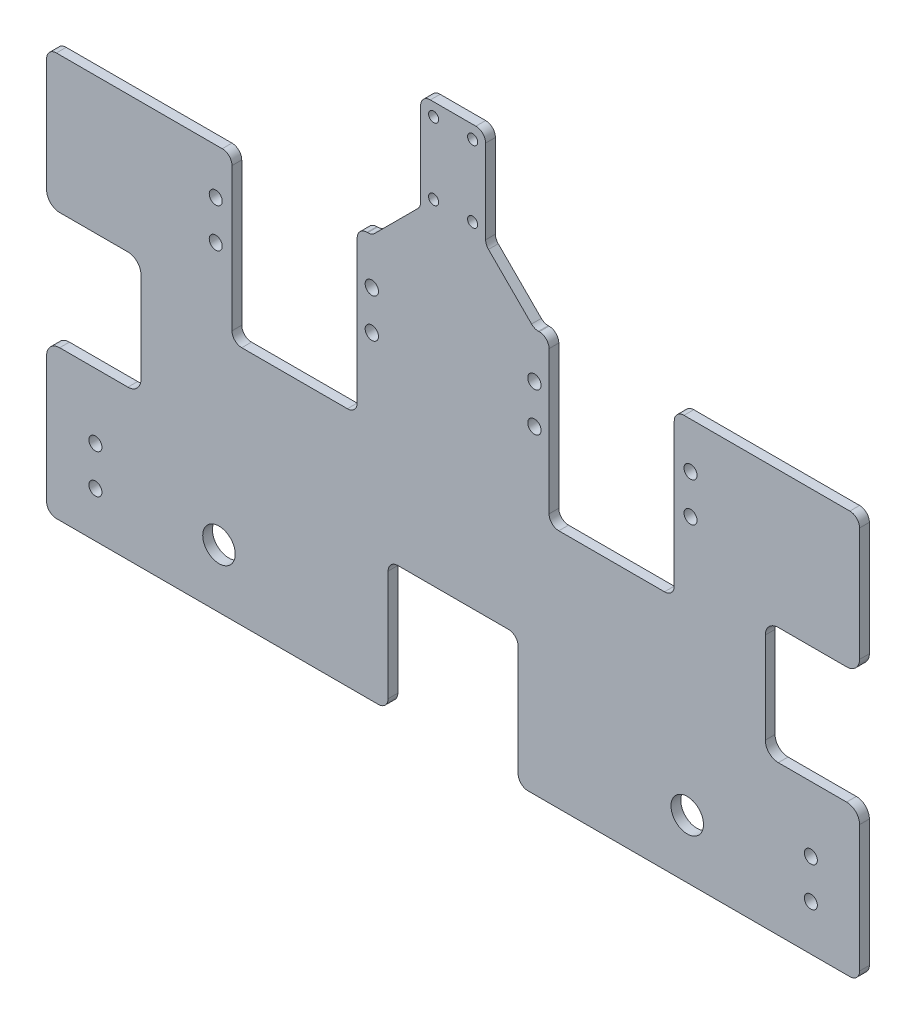
SolidWorks part; units mm, degrees
material "Thornel Mat VMA"
ref_plane "前视基准面" through (0, 0, 0) normal (0, 0, 1) x (1, 0, 0)
ref_plane "上视基准面" through (0, 0, 0) normal (0, 1, 0) x (1, 0, 0)
ref_plane "右视基准面" through (0, 0, 0) normal (1, 0, 0) x (0, 0, -1)
other "Configuration Table"
sketch "草图1" plane through (0, 0, 0) normal (0, 0, 1) x (1, 0, 0)
  line L0 (-32.5, 40) -> (-25, 40)
  line L1 (-25, 40) -> (-10, 55)
  line L2 (-10, 55) -> (-10, 85)
  line L3 (-10, 85) -> (10, 85)
  line L4 (-32.5, 40) -> (-32.5, 0)
  line L5 (-32.5, 0) -> (32.5, 0)
  line L6 (0, 0) -> (0, 50.9699) construction
  line L7 (32.5, 40) -> (32.5, 0)
  line L8 (10, 55) -> (10, 85)
  line L9 (25, 40) -> (10, 55)
  line L10 (32.5, 40) -> (25, 40)
  dimension "D1" = 65
  dimension "D2" = 85
  dimension "D3" = 30
  dimension "D4" = 40
  dimension "D5" = 50
  dimension "D6" = 20
extrude "凸台-拉伸1" add sketch "草图1" along normal blind 3
sketch "草图2" plane through (0, 0, 3) normal (0, 0, 1) x (1, 0, 0)
  line L0 (0, 85) -> (0, 65.679) construction
  line L1 (10, 85) -> (-10, 85) construction
  line L2 (-10, 70) -> (13.1812, 70) construction
  line L3 (-10, 85) -> (-10, 55) construction
  circle A0 centre (-6, 81) radius 1.55
  circle A2 centre (-6, 59) radius 1.55
  circle A3 centre (6, 59) radius 1.55
  circle A4 centre (6, 81) radius 1.55
  dimension "D1" = 4
  dimension "D2" = 4
  dimension "D3" = 3.1
extrude "切除-拉伸1" cut sketch "草图2" against normal through all
sketch "草图3" plane through (0, 0, 3) normal (0, 0, 1) x (1, 0, 0)
  line L0 (32.5, 20) -> (-48.6379, 20) construction
  line L1 (32.5, 0) -> (32.5, 40) construction
  line L2 (0, 0) -> (0, 100.1432) construction
  circle A0 centre (-25, 26) radius 2.05
  circle A2 centre (-25, 14) radius 2.05
  circle A3 centre (25, 14) radius 2.05
  circle A4 centre (25, 26) radius 2.05
  dimension "D1" = 12
  dimension "D2" = 50
  dimension "D3" = 4.1
extrude "切除-拉伸2" cut sketch "草图3" against normal through all
sketch "草图4" plane through (0, 0, 3) normal (0, 0, 1) x (1, 0, 0)
  line L0 (32.5, 0) -> (32.5, 40) construction
  line L1 (32.5, 40) -> (29.5, 40)
  line L2 (32.5, 40) -> (32.5, -0.4765)
  line L3 (32.5, -0.4765) -> (29.5, -0.4765)
  line L4 (29.5, 40) -> (29.5, -0.4765)
  line L5 (0, 85) -> (0, -21.7177) construction
  line L6 (10, 85) -> (-10, 85) construction
  line L7 (-29.5, 40) -> (-29.5, -0.4765)
  line L8 (-32.5, -0.4765) -> (-29.5, -0.4765)
  line L9 (-32.5, 40) -> (-32.5, -0.4765)
  line L10 (-32.5, 40) -> (-29.5, 40)
  dimension "D1" = 3
extrude "切除-拉伸3" cut sketch "草图4" against normal blind 10
sketch "草图5" plane through (0, 0, 3) normal (0, 0, 1) x (1, 0, 0)
  line L0 (0, 0) -> (0, -185.4243) construction
  line L1 (-125, -10) -> (125, -10)
  line L2 (0, 0) -> (0, -84)
  line L3 (-125, -84) -> (125, -84)
  line L4 (125, -10) -> (125, -84)
  line L5 (-125, -10) -> (-125, -84)
  line L6 (-68, -10) -> (-68, 40)
  line L7 (125, -10) -> (68, -10)
  line L8 (125, -10) -> (125, 40)
  line L9 (125, 40) -> (68, 40)
  line L10 (68, -10) -> (68, 40)
  line L11 (-125, 40) -> (-68, 40)
  line L12 (-125, -10) -> (-125, 40)
  line L13 (-125, -10) -> (-68, -10)
  line L14 (-125, -10) -> (-125, -84)
  line L16 (29.5, 40) -> (29.5, 0) construction
  line L17 (-29.5, 0) -> (29.5, 0)
  line L18 (-29.5, 0) -> (-29.5, -10)
  line L19 (-29.5, -10) -> (29.5, -10)
  line L20 (29.5, 0) -> (29.5, -10)
  line M16 (-29.5, 0) -> (29.5, 0)
  dimension "D1" = 250
  dimension "D2" = 50
  dimension "D3" = 68
  dimension "D4" = 74
  dimension "D5" = 10
extrude "凸台-拉伸2" add sketch "草图5" against normal blind 3 contours L10 L1 L8 L9 | L4 L1 L2 L3 | L1 L5 L3 L2 M16 | L12 L1 L6 L11 | L18 L1 L2 M16 | L20 L2 L1 M16
sketch "草图6" plane through (0, 0, 3) normal (0, 0, 1) x (1, 0, 0)
  line L0 (0, 0) -> (0, -103.0936) construction
  line L1 (-125, -84) -> (125, -84) construction
  line L2 (-20, -84) -> (20, -84)
  line L3 (0, -84) -> (0, -44)
  line L4 (-20, -44) -> (20, -44)
  line L5 (20, -84) -> (20, -44)
  line L6 (-20, -84) -> (-20, -44)
  line M14 (-125, -84) -> (125, -84)
  dimension "D1" = 20
  dimension "D2" = 40
extrude "切除-拉伸4" cut sketch "草图6" against normal blind 4 contours L2 L5 L4 L3 | L6 L3 L4 M14
fillet "圆角1" radius 3 22 edges at (-20, -44, 1.5) (20, -44, 1.5) (20, -84, 1.5) (125, -84, 1.5) (68, 40, 1.5) (68, -10, 1.5) (29.5, -10, 1.5) (29.5, 40, 1.5) (25, 40, 1.5) (10, 55, 1.5) (10, 85, 1.5) (-10, 85, 1.5) (-10, 55, 1.5) (-25, 40, 1.5) (-29.5, 40, 1.5) (-29.5, -10, 1.5) (-68, -10, 1.5) (-68, 40, 1.5) (-125, 40, 1.5) (-125, -84, 1.5) (-20, -84, 1.5) (125, 40, 1.5)
sketch "草图7" plane through (0, 0, 3) normal (0, 0, 1) x (1, 0, 0)
  line L0 (125, -81) -> (125, 37) construction
  line L1 (23, -84) -> (122, -84) construction
  line L2 (0, 0) -> (0, -96.374) construction
  line L3 (122, 40) -> (71, 40) construction
  line L4 (96, -2) -> (127, -2)
  line L5 (96, -2) -> (96, -38)
  line L6 (96, -38) -> (127, -38)
  line L7 (127, -2) -> (127, -38)
  line L8 (-127, -2) -> (-127, -38)
  line L9 (-96, -38) -> (-127, -38)
  line L10 (-96, -2) -> (-96, -38)
  line L11 (-96, -2) -> (-127, -2)
  circle A0 centre (72, -66) radius 5
  circle A1 centre (-72, -66) radius 5
  dimension "D1" = 53
  dimension "D2" = 10
  dimension "D3" = 18
  dimension "D4" = 42
  dimension "D5" = 29
  dimension "D6" = 36
  dimension "D7" = 31
extrude "切除-拉伸5" cut sketch "草图7" against normal blind 4
sketch "草图8" plane through (0, 0, 3) normal (0, 0, 1) x (1, 0, 0)
  line L0 (0, 95.4541) -> (0, -92.5342) construction
  line L1 (122, 40) -> (71, 40) construction
  line L2 (125, -2) -> (125, 37) construction
  circle A0 centre (73, 26) radius 2
  circle A1 centre (73, 14) radius 2
  circle A2 centre (-73, 14) radius 2
  circle A3 centre (-73, 26) radius 2
  dimension "D1" = 4
  dimension "D2" = 4
  dimension "D3" = 12
  dimension "D4" = 14
  dimension "D5" = 52
  dimension "D6" = 52
extrude "切除-拉伸6" cut sketch "草图8" against normal blind 4
sketch "草图9" plane through (0, 0, 3) normal (0, 0, 1) x (1, 0, 0)
  line L1 (125, -81) -> (125, -38) construction
  line L2 (0, 116.3395) -> (0, -160.2335) construction
  line L3 (23, -84) -> (122, -84) construction
  circle A0 centre (110, -58) radius 2
  circle A1 centre (110, -70) radius 2
  circle A2 centre (-110, -70) radius 2
  circle A3 centre (-110, -58) radius 2
  dimension "D1" = 4
  dimension "D2" = 4
  dimension "D3" = 12
  dimension "D4" = 14
  dimension "D5" = 15
  dimension "D6" = 15
extrude "切除-拉伸7" cut sketch "草图9" against normal blind 4
fillet "圆角2" radius 4 8 edges at (-125, -38, 1.5) (-125, -2, 1.5) (125, -38, 1.5) (125, -2, 1.5) (-96, -2, 1.5) (-96, -38, 1.5) (96, -38, 1.5) (96, -2, 1.5)
